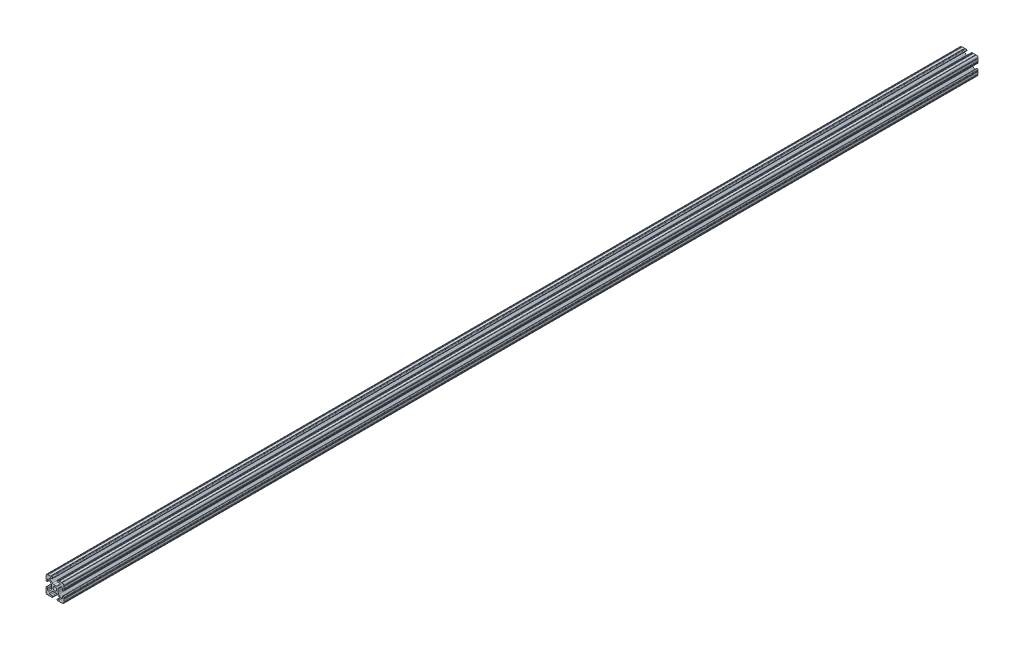
SolidWorks part; units mm, degrees
ref_plane "Front Plane" through (0, 0, 0) normal (0, 0, 1) x (1, 0, 0)
ref_plane "Top Plane" through (0, 0, 0) normal (0, 1, 0) x (1, 0, 0)
ref_plane "Right Plane" through (0, 0, 0) normal (1, 0, 0) x (0, 0, -1)
sketch "Sketch1" plane through (0, 0, 0) normal (0, 0, 1) x (1, 0, 0)
  line L88 (-7.1797, -8.6452) -> (-3.9523, -5.4237)
  line L89 (-1.7093, -4.4958) -> (1.7093, -4.4958)
  line L90 (3.9523, -5.4237) -> (7.1797, -8.6452)
  line L91 (6.4164, -10.4902) -> (4.2875, -10.4902)
  line L92 (3.2385, -11.5392) -> (3.2385, -11.651)
  line L93 (4.2875, -12.7) -> (5.3171, -12.7)
  line L94 (6.3331, -12.7) -> (9.5504, -12.7)
  line L95 (12.7, -9.5504) -> (12.7, -6.3331)
  line L96 (12.7, -5.3171) -> (12.7, -4.2875)
  line L97 (11.651, -3.2385) -> (11.5392, -3.2385)
  line L98 (10.4902, -4.2875) -> (10.4902, -6.4021)
  line L99 (8.7371, -7.1294) -> (5.441, -3.8408)
  line L100 (4.5085, -1.5932) -> (4.5085, 1.5932)
  line L101 (5.441, 3.8408) -> (8.7371, 7.1294)
  line L102 (10.4902, 6.4021) -> (10.4902, 4.2875)
  line L103 (11.5392, 3.2385) -> (11.651, 3.2385)
  line L104 (12.7, 4.2875) -> (12.7, 5.3171)
  line L105 (12.7, 6.3331) -> (12.7, 9.5504)
  line L106 (9.5504, 12.7) -> (6.3331, 12.7)
  line L107 (5.3171, 12.7) -> (4.2875, 12.7)
  line L108 (3.2385, 11.651) -> (3.2385, 11.5392)
  line L109 (4.2875, 10.4902) -> (6.4768, 10.4902)
  line L110 (7.207, 8.7244) -> (3.8983, 5.4232)
  line L111 (1.6558, 4.4958) -> (-1.6558, 4.4958)
  line L112 (-3.8983, 5.4232) -> (-7.207, 8.7244)
  line L113 (-6.4768, 10.4902) -> (-4.2875, 10.4902)
  line L114 (-3.2385, 11.5392) -> (-3.2385, 11.651)
  line L115 (-4.2875, 12.7) -> (-5.3171, 12.7)
  line L116 (-6.3331, 12.7) -> (-9.5504, 12.7)
  line L117 (-12.7, 9.5504) -> (-12.7, 6.3331)
  line L118 (-12.7, 5.3171) -> (-12.7, 4.2875)
  line L119 (-11.651, 3.2385) -> (-11.5392, 3.2385)
  line L120 (-10.4902, 4.2875) -> (-10.4902, 6.4021)
  line L121 (-8.7371, 7.1294) -> (-5.441, 3.8408)
  line L122 (-4.5085, 1.5932) -> (-4.5085, -1.5932)
  line L123 (-5.441, -3.8408) -> (-8.7371, -7.1294)
  line L124 (-10.4902, -6.4021) -> (-10.4902, -4.2875)
  line L125 (-11.5392, -3.2385) -> (-11.651, -3.2385)
  line L126 (-12.7, -4.2875) -> (-12.7, -5.3171)
  line L127 (-12.7, -6.3331) -> (-12.7, -9.5504)
  line L128 (-9.5504, -12.7) -> (-6.3331, -12.7)
  line L129 (-5.3171, -12.7) -> (-4.2875, -12.7)
  line L130 (-3.2385, -11.651) -> (-3.2385, -11.5392)
  line L131 (-4.2875, -10.4902) -> (-6.4164, -10.4902)
  circle A1 centre (0, 0) radius 2.6035
  arc A104 (-7.1797, -8.6452) -> (-6.4164, -10.4902) centre (-6.4164, -9.4098) ccw
  arc A105 (-1.7093, -4.4958) -> (-3.9523, -5.4237) centre (-1.7093, -7.6708) ccw
  arc A106 (3.9523, -5.4237) -> (1.7093, -4.4958) centre (1.7093, -7.6708) ccw
  arc A107 (6.4164, -10.4902) -> (7.1797, -8.6452) centre (6.4164, -9.4098) ccw
  arc A108 (4.2875, -10.4902) -> (3.2385, -11.5392) centre (4.2875, -11.5392) ccw
  arc A109 (3.2385, -11.651) -> (4.2875, -12.7) centre (4.2875, -11.651) ccw
  arc A110 (6.3331, -12.7) -> (5.3171, -12.7) centre (5.8251, -12.7) ccw
  arc A111 (10.5664, -12.6998) -> (9.5504, -12.7) centre (10.0584, -12.7) ccw
  arc A112 (10.5664, -12.6998) -> (12.6998, -10.5664) centre (10.5918, -10.5918) ccw
  arc A113 (12.7, -9.5504) -> (12.6998, -10.5664) centre (12.7, -10.0584) ccw
  arc A114 (12.7, -5.3171) -> (12.7, -6.3331) centre (12.7, -5.8251) ccw
  arc A115 (12.7, -4.2875) -> (11.651, -3.2385) centre (11.651, -4.2875) ccw
  arc A116 (11.5392, -3.2385) -> (10.4902, -4.2875) centre (11.5392, -4.2875) ccw
  arc A117 (8.7371, -7.1294) -> (10.4902, -6.4021) centre (9.4628, -6.4021) ccw
  arc A118 (4.5085, -1.5932) -> (5.441, -3.8408) centre (7.6835, -1.5932) ccw
  arc A119 (5.441, 3.8408) -> (4.5085, 1.5932) centre (7.6835, 1.5932) ccw
  arc A120 (10.4902, 6.4021) -> (8.7371, 7.1294) centre (9.4628, 6.4021) ccw
  arc A121 (10.4902, 4.2875) -> (11.5392, 3.2385) centre (11.5392, 4.2875) ccw
  arc A122 (11.651, 3.2385) -> (12.7, 4.2875) centre (11.651, 4.2875) ccw
  arc A123 (12.7, 6.3331) -> (12.7, 5.3171) centre (12.7, 5.8251) ccw
  arc A124 (12.6998, 10.5664) -> (12.7, 9.5504) centre (12.7, 10.0584) ccw
  arc A125 (12.6998, 10.5664) -> (10.5664, 12.6998) centre (10.5918, 10.5918) ccw
  arc A126 (9.5504, 12.7) -> (10.5664, 12.6998) centre (10.0584, 12.7) ccw
  arc A127 (5.3171, 12.7) -> (6.3331, 12.7) centre (5.8251, 12.7) ccw
  arc A128 (4.2875, 12.7) -> (3.2385, 11.651) centre (4.2875, 11.651) ccw
  arc A129 (3.2385, 11.5392) -> (4.2875, 10.4902) centre (4.2875, 11.5392) ccw
  arc A130 (7.207, 8.7244) -> (6.4768, 10.4902) centre (6.4768, 9.4563) ccw
  arc A131 (1.6558, 4.4958) -> (3.8983, 5.4232) centre (1.6558, 7.6708) ccw
  arc A132 (-3.8983, 5.4232) -> (-1.6558, 4.4958) centre (-1.6558, 7.6708) ccw
  arc A133 (-6.4768, 10.4902) -> (-7.207, 8.7244) centre (-6.4768, 9.4563) ccw
  arc A134 (-4.2875, 10.4902) -> (-3.2385, 11.5392) centre (-4.2875, 11.5392) ccw
  arc A135 (-3.2385, 11.651) -> (-4.2875, 12.7) centre (-4.2875, 11.651) ccw
  arc A136 (-6.3331, 12.7) -> (-5.3171, 12.7) centre (-5.8251, 12.7) ccw
  arc A137 (-10.5664, 12.6998) -> (-9.5504, 12.7) centre (-10.0584, 12.7) ccw
  arc A138 (-10.5664, 12.6998) -> (-12.6998, 10.5664) centre (-10.5918, 10.5918) ccw
  arc A139 (-12.7, 9.5504) -> (-12.6998, 10.5664) centre (-12.7, 10.0584) ccw
  arc A140 (-12.7, 5.3171) -> (-12.7, 6.3331) centre (-12.7, 5.8251) ccw
  arc A141 (-12.7, 4.2875) -> (-11.651, 3.2385) centre (-11.651, 4.2875) ccw
  arc A142 (-11.5392, 3.2385) -> (-10.4902, 4.2875) centre (-11.5392, 4.2875) ccw
  arc A143 (-8.7371, 7.1294) -> (-10.4902, 6.4021) centre (-9.4628, 6.4021) ccw
  arc A144 (-4.5085, 1.5932) -> (-5.441, 3.8408) centre (-7.6835, 1.5932) ccw
  arc A145 (-5.441, -3.8408) -> (-4.5085, -1.5932) centre (-7.6835, -1.5932) ccw
  arc A146 (-10.4902, -6.4021) -> (-8.7371, -7.1294) centre (-9.4628, -6.4021) ccw
  arc A147 (-10.4902, -4.2875) -> (-11.5392, -3.2385) centre (-11.5392, -4.2875) ccw
  arc A148 (-11.651, -3.2385) -> (-12.7, -4.2875) centre (-11.651, -4.2875) ccw
  arc A149 (-12.7, -6.3331) -> (-12.7, -5.3171) centre (-12.7, -5.8251) ccw
  arc A150 (-12.6998, -10.5664) -> (-12.7, -9.5504) centre (-12.7, -10.0584) ccw
  arc A151 (-12.6998, -10.5664) -> (-10.5664, -12.6998) centre (-10.5918, -10.5918) ccw
  arc A152 (-9.5504, -12.7) -> (-10.5664, -12.6998) centre (-10.0584, -12.7) ccw
  arc A153 (-5.3171, -12.7) -> (-6.3331, -12.7) centre (-5.8251, -12.7) ccw
  arc A154 (-4.2875, -12.7) -> (-3.2385, -11.651) centre (-4.2875, -11.651) ccw
  arc A155 (-3.2385, -11.5392) -> (-4.2875, -10.4902) centre (-4.2875, -11.5392) ccw
extrude "Boss-Extrude1" add sketch "Sketch1" along normal mid plane 1303.3375
